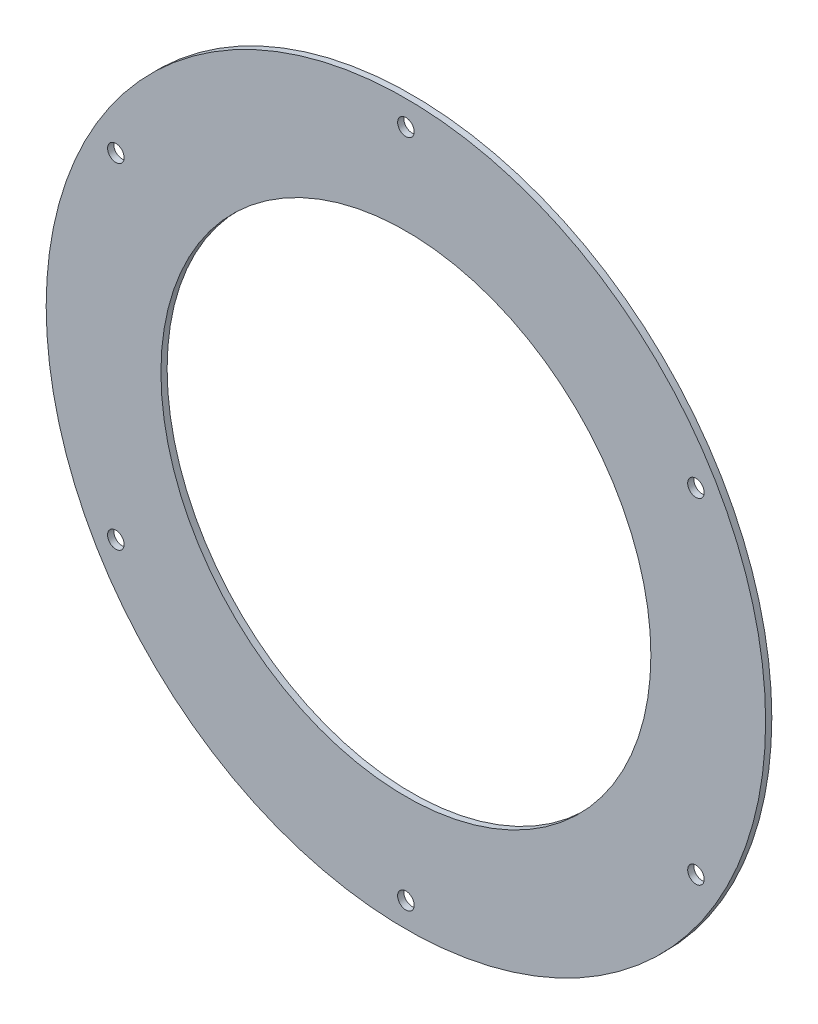
SolidWorks part; units mm, degrees
ref_plane "Front Plane" through (0, 0, 0) normal (0, 0, 1) x (1, 0, 0)
ref_plane "Top Plane" through (0, 0, 0) normal (0, 1, 0) x (1, 0, 0)
ref_plane "Right Plane" through (0, 0, 0) normal (1, 0, 0) x (0, 0, -1)
sketch "Sketch1" plane through (0, 0, 0) normal (0, 0, 1) x (1, 0, 0)
  line L0 (0, 174) -> (0, 162) construction
  circle A0 centre (0, 0) radius 174
  circle A1 centre (0, 162) radius 4
  circle A2 centre (140.2961, 81) radius 4
  circle A3 centre (140.2961, -81) radius 4
  circle A4 centre (0, -162) radius 4
  circle A5 centre (-140.2961, -81) radius 4
  circle A6 centre (-140.2961, 81) radius 4
  circle A7 centre (0, 0) radius 118.5
  point P19 (0, 0)
  dimension "D1" = 348
  dimension "D3" = 8
  dimension "D5" = 237
  dimension "D2" = 12
  dimension "D4" = 6
extrude "Boss-Extrude1" add sketch "Sketch1" along normal blind 3
equation "\"acTubeOD\"= 300mm"
equation "\"acTubeThickness\"= 3mm"
equation "\"acTubeLength\"= 300mm"
equation "\"threadedRodDiam\"= 8mm"
equation "\"flange width\"= 24mm"
equation "\"D1@Sketch1\"=\"acTubeOD\" + \"flange width\"*2"
